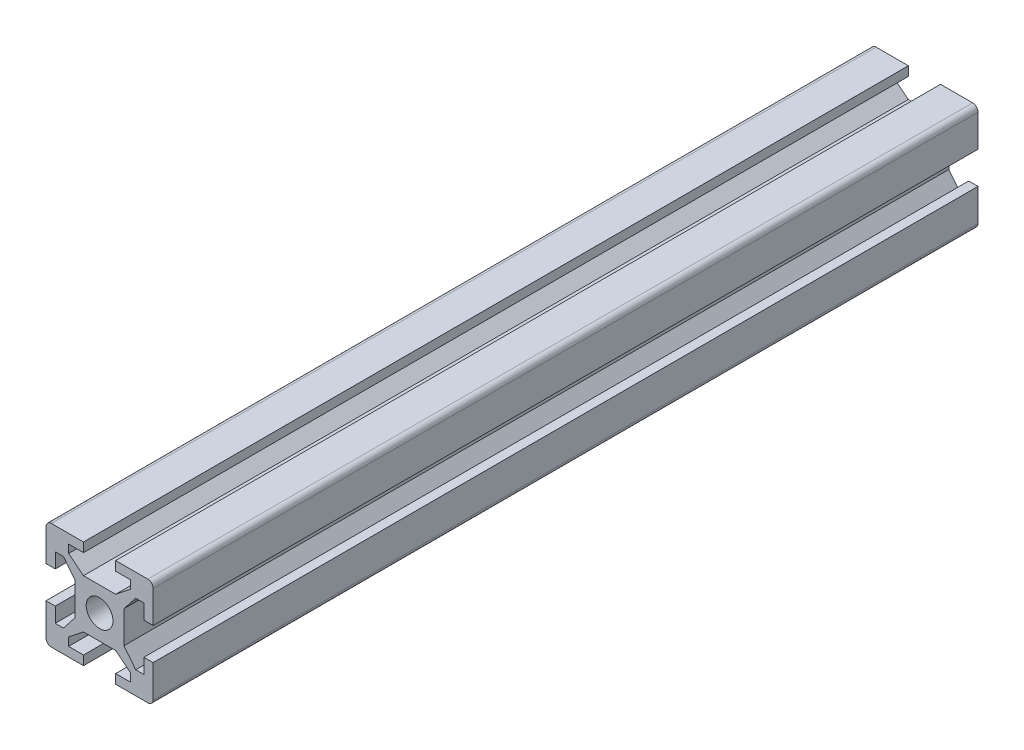
SolidWorks part; units mm, degrees
material "6063-T5"
ref_plane "Front Plane" through (0, 0, 0) normal (0, 0, 1) x (1, 0, 0)
ref_plane "Top Plane" through (0, 0, 0) normal (0, 1, 0) x (1, 0, 0)
ref_plane "Right Plane" through (0, 0, 0) normal (1, 0, 0) x (0, 0, -1)
sketch "Sketch1" plane through (0, 0, 0) normal (0, 0, 1) x (1, 0, 0)
  line L18 (0, 0) -> (0, 20.5117) construction
  line L39 (-10, 10) -> (-3, 10)
  line L41 (10, 10) -> (3, 10)
  line L43 (-10, 10) -> (-10, 3)
  line L45 (-10, -10) -> (-10, -3)
  line L47 (-10, -10) -> (-3, -10)
  line L49 (3, -10) -> (10, -10)
  line L51 (10, -10) -> (10, -3)
  line L53 (10, 3) -> (10, 10)
  line L55 (-3, 10) -> (-3, 8.2726)
  line L56 (-3, 8.2726) -> (-5.7838, 8.2726)
  line L57 (-5.7838, 8.2726) -> (-5.7838, 6.748)
  line L58 (-5.7838, 6.748) -> (-3, 4.5508)
  line L59 (-3, 4.5508) -> (3, 4.5508)
  line L60 (3, 10) -> (3, 8.2726)
  line L61 (3, 8.2726) -> (5.7838, 8.2726)
  line L62 (5.7838, 8.2726) -> (5.7838, 6.748)
  line L63 (5.7838, 6.748) -> (3, 4.5508)
  line L64 (10, 3) -> (8.2726, 3)
  line L65 (8.2726, 3) -> (8.2726, 5.7838)
  line L66 (8.2726, 5.7838) -> (6.748, 5.7838)
  line L67 (10, -3) -> (8.2726, -3)
  line L68 (8.2726, -3) -> (8.2726, -5.7838)
  line L69 (8.2726, -5.7838) -> (6.748, -5.7838)
  line L70 (4.55, -2.9994) -> (4.55, 3.0006)
  line L71 (4.55, -2.9994) -> (6.748, -5.7838)
  line L72 (4.55, 3.0006) -> (6.748, 5.7838)
  line L73 (3, -10) -> (3, -8.2726)
  line L74 (3, -8.2726) -> (5.7838, -8.2726)
  line L75 (5.7838, -8.2726) -> (5.7838, -6.748)
  line L76 (-3, -10) -> (-3, -8.2726)
  line L77 (-3, -8.2726) -> (-5.7838, -8.2726)
  line L78 (-5.7838, -8.2726) -> (-5.7838, -6.748)
  line L79 (2.9994, -4.55) -> (-3.0006, -4.55)
  line L80 (5.7838, -6.748) -> (2.9994, -4.55)
  line L81 (-5.7838, -6.748) -> (-3.0006, -4.55)
  line L82 (-10, -3) -> (-8.2726, -3)
  line L83 (-8.2726, -3) -> (-8.2726, -5.7838)
  line L84 (-8.2726, -5.7838) -> (-6.748, -5.7838)
  line L85 (-10, 3) -> (-8.2726, 3)
  line L86 (-8.2726, 3) -> (-8.2726, 5.7838)
  line L87 (-8.2726, 5.7838) -> (-6.748, 5.7838)
  line L88 (-4.55, -3.0006) -> (-4.55, 2.9994)
  line L89 (-6.748, -5.7838) -> (-4.55, -3.0006)
  line L90 (-4.55, 2.9994) -> (-6.748, 5.7838)
  dimension "D9" = 7
  dimension "D17" = 2.7838
  dimension "D1" = 20
  dimension "D2" = 20
  dimension "D3" = 10
  dimension "D4" = 10
  dimension "D5" = 7
  dimension "D6" = 7
  dimension "D7" = 7
  dimension "D8" = 7
  dimension "D10" = 7
  dimension "D11" = 7
  dimension "D12" = 7
  dimension "D13" = 6
  dimension "D14" = 3
  dimension "D15" = 3.5464
  dimension "D16" = 1.5246
  dimension "D18" = 1.7274
  dimension "D19" = 4.55
  dimension "D20" = 4.55
  dimension "D21" = 4.55
  dimension "D22" = 10
  dimension "D23" = 10
  dimension "D24" = 10
  dimension "D25" = 10
  dimension "D26" = 10
  dimension "D27" = 10
  dimension "D28" = 6
  dimension "D29" = 6
  dimension "D30" = 6
  dimension "D31" = 6
extrude "Boss-Extrude1" add sketch "Sketch1" along normal mid plane 154
sketch "Sketch2" plane through (0, 0, 77) normal (0, 0, 1) x (1, 0, 0)
  circle A0 centre (0, 0) radius 2.5
  dimension "D1" = 5
extrude "Cut-Extrude1" cut sketch "Sketch2" against normal through all both and the other way through all
fillet "Fillet1" radius 1 4 edges at (-10, -10, 0) (10, -10, 0) (10, 10, 0) (-10, 10, 0)
